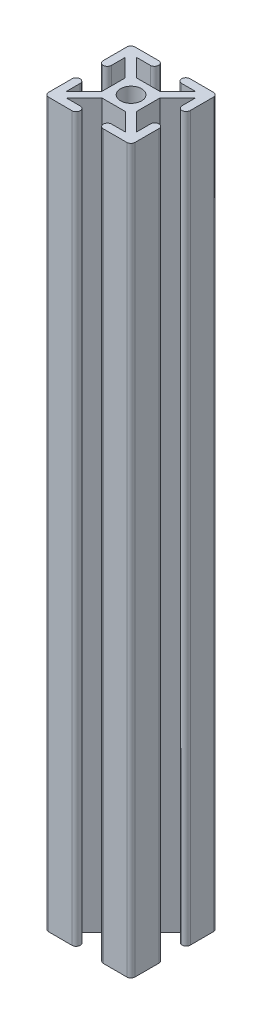
SolidWorks part; units mm, degrees
ref_plane "Alzado" through (0, 0, 0) normal (0, 0, 1) x (1, 0, 0)
ref_plane "Planta" through (0, 0, 0) normal (0, 1, 0) x (1, 0, 0)
ref_plane "Vista lateral" through (0, 0, 0) normal (1, 0, 0) x (0, 0, -1)
sketch "Croquis1" plane through (0, 0, 0) normal (0, 1, 0) x (1, 0, 0)
  line L0 (-7.576, 9.4366) -> (-7.576, 10.8616) construction
  line L1 (11.4769, -6.7134) -> (16.2019, -6.7134)
  line L2 (-9.001, 19.0116) -> (-9.001, 10.8616)
  line L3 (-7.576, 20.4366) -> (0.574, 20.4366)
  line L4 (11.424, 20.4366) -> (19.574, 20.4366)
  line L5 (-4.0981, -6.7134) -> (0.6269, -6.7134)
  line L6 (-0.001, 9.4366) -> (-0.001, 1.4366)
  line L7 (-8.9481, 0.0116) -> (-8.9481, -8.1384)
  line L8 (-7.5495, -9.5369) -> (0.6269, -9.5634)
  line L9 (20.999, 19.0116) -> (20.999, 10.9653)
  line L10 (-6.151, 15.5866) -> (-6.151, 10.8616)
  line L11 (20.999, 0.1153) -> (20.999, -8.1384)
  line L12 (1.999, 19.0116) -> (0.574, 19.0116) construction
  line L13 (11.4769, -9.5634) -> (19.574, -9.5634)
  line L14 (-4.151, 17.5866) -> (0.574, 17.5866)
  line L15 (-6.151, 0.0116) -> (-6.151, -4.7134)
  line L16 (9.999, 19.0116) -> (11.424, 19.0116) construction
  line L17 (11.424, 17.5866) -> (16.149, 17.5866)
  line L18 (19.574, 9.5403) -> (19.574, 10.9653) construction
  line L19 (1.999, 11.4366) -> (-4.151, 17.5866)
  line L20 (18.149, 15.5866) -> (18.149, 10.9653)
  line L21 (19.574, 1.5403) -> (19.574, 0.1153) construction
  line L22 (-0.001, 9.4366) -> (-6.151, 15.5866)
  line L23 (18.149, 0.1153) -> (18.149, -4.7134)
  line L24 (10.0519, -8.1384) -> (11.4769, -8.1384) construction
  line L25 (-0.001, 1.4366) -> (-6.151, -4.7134)
  line L26 (1.999, 11.4366) -> (9.999, 11.4366)
  line L27 (9.999, 11.4366) -> (16.149, 17.5866)
  line L28 (-7.5495, 1.4366) -> (-7.5495, 0.0116) construction
  line L29 (-4.0981, -6.7134) -> (2.0519, -0.5634)
  line L30 (2.0519, -0.5634) -> (10.0519, -0.5634)
  line L31 (10.0519, -0.5634) -> (16.2019, -6.7134)
  line L32 (2.0519, -8.1384) -> (0.6269, -8.1384) construction
  line L33 (11.999, 1.4366) -> (18.149, -4.7134)
  line L34 (11.999, 9.4366) -> (18.149, 15.5866)
  line L35 (11.999, 9.4366) -> (11.999, 1.4366)
  circle A0 centre (6.0519, 5.4366) radius 3.645
  arc A1 (-9.001, 10.8616) -> (-6.151, 10.8616) centre (-7.576, 10.8616) ccw
  arc A2 (0.574, 17.5866) -> (0.574, 20.4366) centre (0.574, 19.0116) ccw
  arc A3 (11.424, 20.4366) -> (11.424, 17.5866) centre (11.424, 19.0116) ccw
  arc A4 (18.149, 10.9653) -> (20.999, 10.9653) centre (19.574, 10.9653) ccw
  arc A5 (20.999, 0.1153) -> (18.149, 0.1153) centre (19.574, 0.1153) ccw
  arc A6 (11.4769, -6.7134) -> (11.4769, -9.5634) centre (11.4769, -8.1384) ccw
  arc A7 (-6.151, 0.0116) -> (-8.9481, 0.0116) centre (-7.5495, 0.0116) ccw
  arc A8 (0.6269, -9.5634) -> (0.6269, -6.7134) centre (0.6269, -8.1384) ccw
  arc A9 (-8.9481, -8.1384) -> (-7.5495, -9.5369) centre (-7.5495, -8.1384) ccw
  arc A10 (19.574, -9.5634) -> (20.999, -8.1384) centre (19.574, -8.1384) ccw
  arc A11 (20.999, 19.0116) -> (19.574, 20.4366) centre (19.574, 19.0116) ccw
  arc A12 (-7.576, 20.4366) -> (-9.001, 19.0116) centre (-7.576, 19.0116) ccw
  dimension "D1" = 7.29
  dimension "D2" = 1.425
  dimension "D3" = 1.425
  dimension "D4" = 1.425
  dimension "D5" = 1.425
  dimension "D6" = 1.425
  dimension "D7" = 1.425
  dimension "D8" = 1.425
  dimension "D9" = 1.425
extrude "Saliente-Extruir1" add sketch "Croquis1" along normal blind 250
